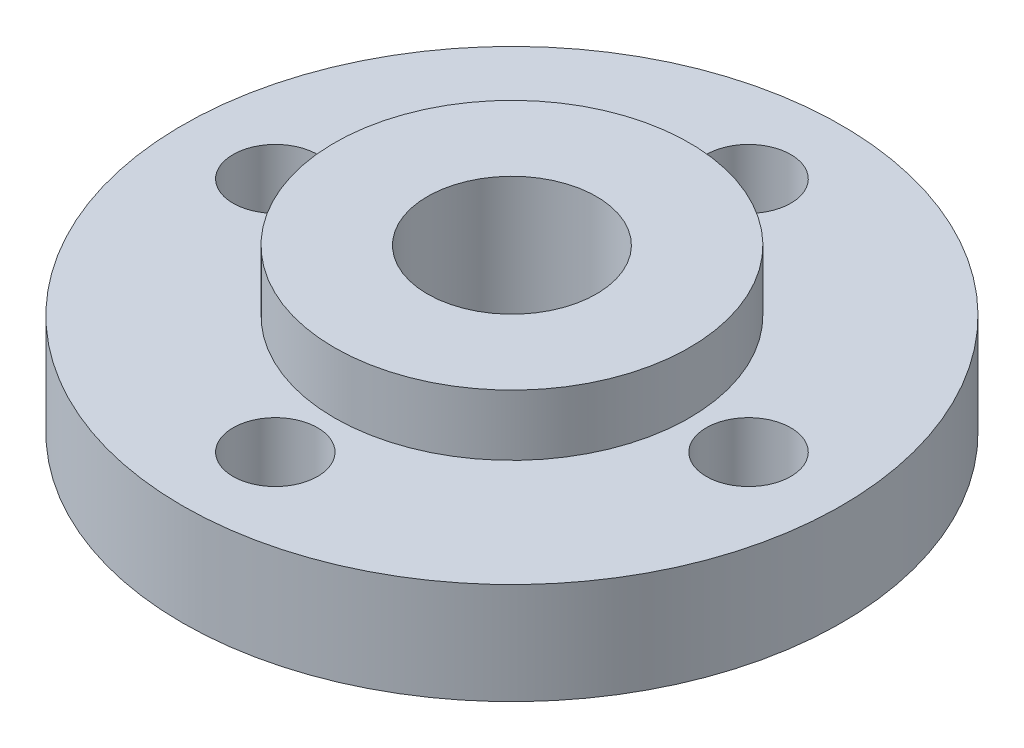
SolidWorks part; units mm, degrees
material "6061 合金"
ref_plane "前视基准面" through (0, 0, 0) normal (0, 0, 1) x (1, 0, 0)
ref_plane "上视基准面" through (0, 0, 0) normal (0, 1, 0) x (1, 0, 0)
ref_plane "右视基准面" through (0, 0, 0) normal (1, 0, 0) x (0, 0, -1)
sketch "草图1" plane through (0, 0, 0) normal (0, 1, 0) x (1, 0, 0)
  circle A0 centre (0, 0) radius 9.75
  dimension "D1" = 19.5
extrude "凸台-拉伸1" add sketch "草图1" along normal blind 3
sketch "草图2" plane through (0, 3, 0) normal (0, 1, 0) x (1, 0, 0)
  circle A0 centre (0, 0) radius 5.25
  dimension "D1" = 10.5
extrude "凸台-拉伸2" add sketch "草图2" along normal blind 1.8
sketch "草图3" plane through (0, 4.8, 0) normal (0, 1, 0) x (1, 0, 0)
  circle A0 centre (0, 0) radius 2.5
  dimension "D1" = 5
extrude "切除-拉伸1" cut sketch "草图3" against normal blind 3.7
sketch "草图7" plane through (0, 3, 0) normal (0, 1, 0) x (1, 0, 0)
  circle A0 centre (0, 0) radius 7
  dimension "D1" = 14
hole_wizard "M3 螺纹孔1" positions "草图9" profile "草图8" tap size "M3" standard "GB"
sketch "草图9" plane through (0, 3, 0) normal (0, 1, 0) x (1, 0, 0)
  circle A0 centre (0, 0) radius 7 construction
  point P0 (0, 7)
  point P4 (7, 0)
  point P6 (0, -7)
  point P8 (-7, 0)
  dimension "D1" = 7
sketch "草图8" plane through (0, 3, -7) normal (1, 0, 0) x (0, 0, 1)
  line L0 (0, 0) -> (0, 9.2511)
  line L1 (0, 9.2511) -> (1.25, 8.5)
  line L2 (1.25, 8.5) -> (1.25, 0)
  line L5 (1.25, 0) -> (0, 0)
  line L10 (0, 9.2511) -> (-1.25, 8.5) construction
  line L11 (0, -6.35) -> (0, 107.95) construction
  dimension "螺纹孔钻头直径" = 2.5
  dimension "螺纹孔钻头深度" = 8.5
  dimension "导头角度" = 118
cosmetic thread "孔螺蚊线1" parameters "D1"=3, "D2"=3
cosmetic thread "孔螺蚊线2" parameters "D1"=3, "D2"=3
cosmetic thread "孔螺蚊线3" parameters "D1"=3, "D2"=3
cosmetic thread "孔螺蚊线4" parameters "D1"=3, "D2"=3
sketch "草图10" plane through (0, 1.1, 0) normal (0, 1, 0) x (1, 0, 0)
  circle A0 centre (0, 0) radius 1.5
  dimension "D1" = 3
extrude "切除-拉伸2" cut sketch "草图10" against normal blind 3.7
